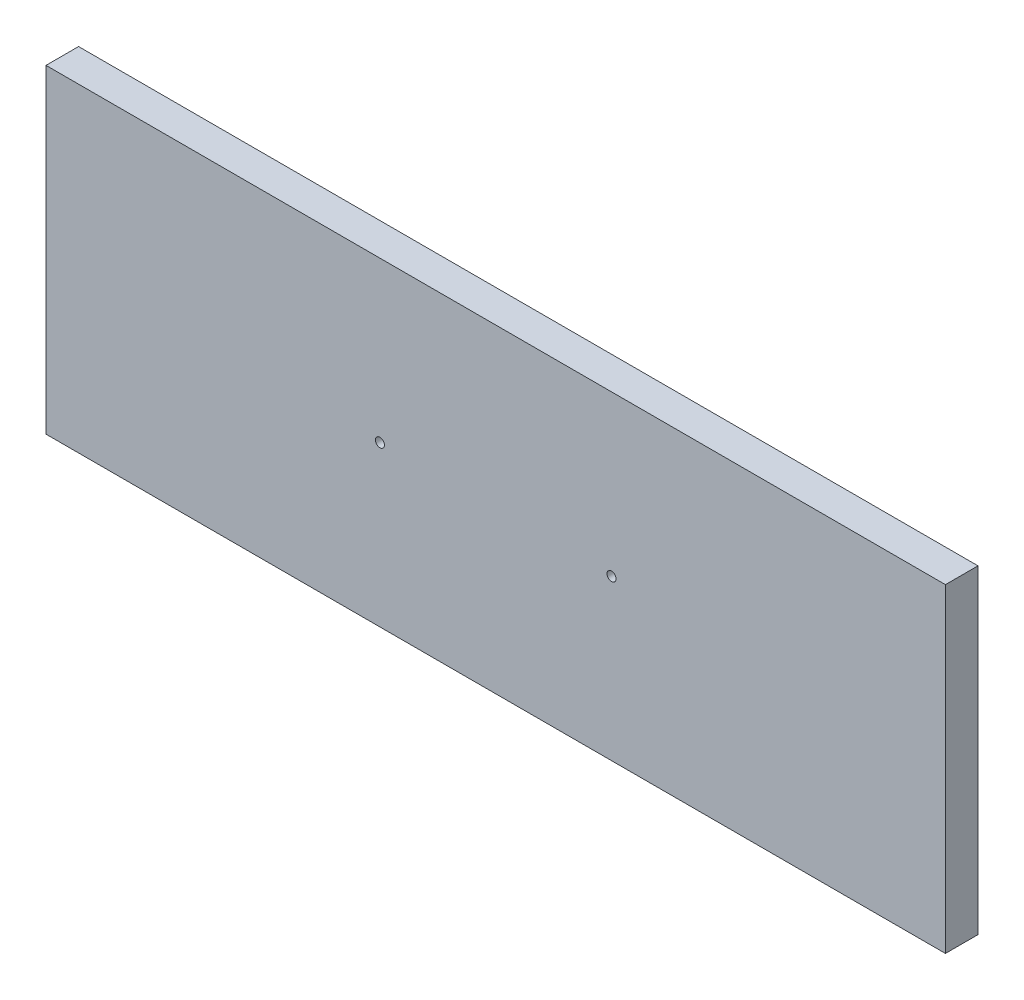
SolidWorks part; units mm, degrees
ref_plane "Front Plane" through (0, 0, 0) normal (0, 0, 1) x (1, 0, 0)
ref_plane "Top Plane" through (0, 0, 0) normal (0, 1, 0) x (1, 0, 0)
ref_plane "Right Plane" through (0, 0, 0) normal (1, 0, 0) x (0, 0, -1)
sketch "Sketch1" plane through (0, 0, 0) normal (0, 0, 1) x (1, 0, 0)
  line L0 (-248.5, -573.5) -> (-248.5, -750) construction
  line L1 (248.5, -750) -> (-248.5, -750) construction
  line L2 (248.5, -573.5) -> (248.5, -750) construction
  line L3 (248.5, -573.5) -> (-248.5, -573.5) construction
  line L4 (-248.5, -573.5) -> (-248.5, -750)
  line L5 (248.5, -750) -> (-248.5, -750)
  line L6 (248.5, -573.5) -> (248.5, -750)
  line L7 (248.5, -573.5) -> (-248.5, -573.5)
  dimension "D1" = 497
  dimension "D2" = 176.5
extrude "Boss-Extrude1" add sketch "Sketch1" along normal blind 18
extrude "Cut-Extrude2" cut sketch "Sketch3" along normal blind 61
sketch "Sketch3" plane through (0, 0, 0) normal (0, 0, 1) x (1, 0, 0)
  line L1 (248.5, -573.5) -> (-248.5, -573.5)
  line L2 (248.5, -573.5) -> (248.5, -750)
  line L3 (248.5, -750) -> (-248.5, -750)
  line L4 (-248.5, -573.5) -> (-248.5, -750)
  line L7 (0, -573.5) -> (0, -750) construction
  circle A0 centre (64, -661.75) radius 2.5
  circle A1 centre (-64, -661.75) radius 2.5
sketch "Sketch4" plane through (0, 0, 0) normal (0, 0, -1) x (-1, 0, 0)
  line L0 (248.5, -573.5) -> (248.5, -750) construction
  line L1 (-248.5, -573.5) -> (248.5, -573.5) construction
  circle A0 centre (148.5, -608.5) radius 10
  dimension "D1" = 20
  dimension "D2" = 100
  dimension "D3" = 35
extrude "Cut-Extrude3" [suppressed] cut sketch "Sketch4" against normal through all
sketch "Sketch5" plane through (0, 0, 18) normal (0, 0, 1) x (1, 0, 0)
  line L0 (0, -573.5) -> (0, -750) construction
  line L1 (248.5, -573.5) -> (-248.5, -573.5) construction
  line L2 (-248.5, -750) -> (248.5, -750) construction
  circle A0 centre (-230.589, -671.5) radius 5
  circle A1 centre (230.589, -671.5) radius 5
  circle A2 centre (-230.589, -735.5) radius 5
  circle A3 centre (230.589, -735.5) radius 5
  dimension "D1" = 2
  dimension "D2" = 10
  dimension "D3" = 64
  dimension "D4" = 14.5
extrude "Cut-Extrude4" [suppressed] cut sketch "Sketch5" against normal blind 12
